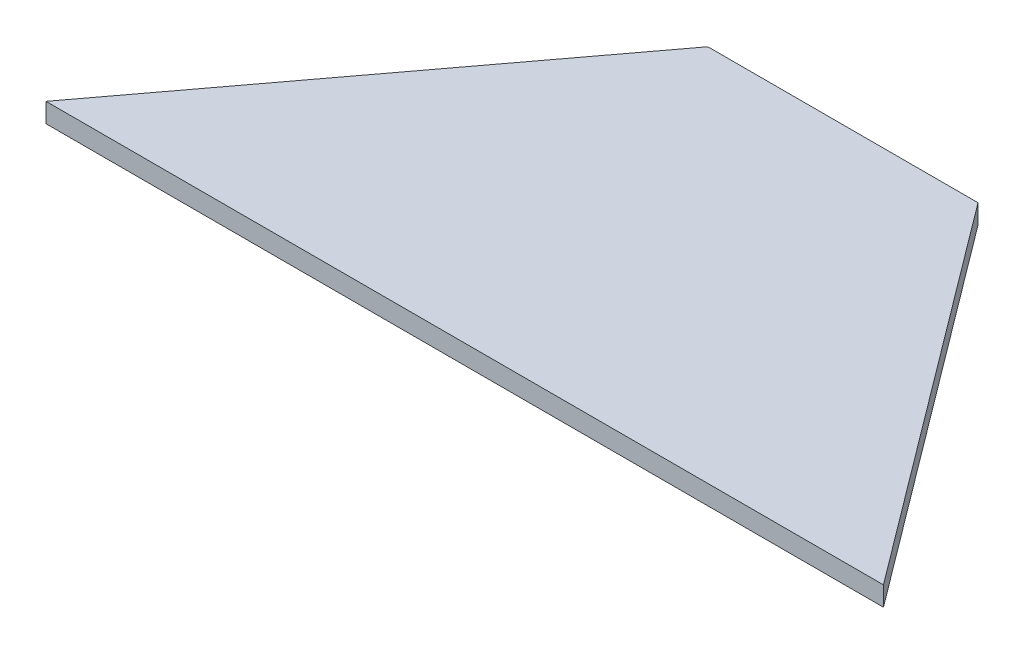
SolidWorks part; units mm, degrees
material "Pine"
ref_plane "Front Plane" through (0, 0, 0) normal (0, 0, 1) x (1, 0, 0)
ref_plane "Top Plane" through (0, 0, 0) normal (0, 1, 0) x (1, 0, 0)
ref_plane "Right Plane" through (0, 0, 0) normal (1, 0, 0) x (0, 0, -1)
sketch "Sketch1" plane through (0, 0, 0) normal (0, 1, 0) x (1, 0, 0)
  line L0 (-127, -1130.3) -> (127, -1130.3)
  line L1 (-127, 0) -> (127, 0)
  line L2 (-127, 0) -> (-127, -482.6)
  line L3 (-127, -482.6) -> (127, -482.6) construction
  line L4 (127, 0) -> (127, -482.6)
  line L5 (127, -1130.3) -> (393.7, -1485.9)
  line L6 (393.7, -1485.9) -> (-393.7, -1485.9)
  line L7 (-393.7, -1485.9) -> (-127, -1130.3)
  line L9 (-127, -1130.3) -> (127, -1130.3) construction
  line L10 (-127, -1130.3) -> (-127, -482.6)
  line L11 (-127, -482.6) -> (127, -482.6)
  line L12 (127, -1130.3) -> (127, -482.6)
  point P4 (0, 0)
  point P6 (0, -1485.9)
  dimension "D1" = 254
  dimension "D2" = 1485.9
  dimension "D3" = 787.4
  dimension "D4" = 355.6
  dimension "D5" = 1003.3
  dimension "D6" = 1130.3
extrude "Boss-Extrude2" add sketch "Sketch1" along normal blind 18.2562 separate body contours L5 L12 L3 L10 L7 L6
